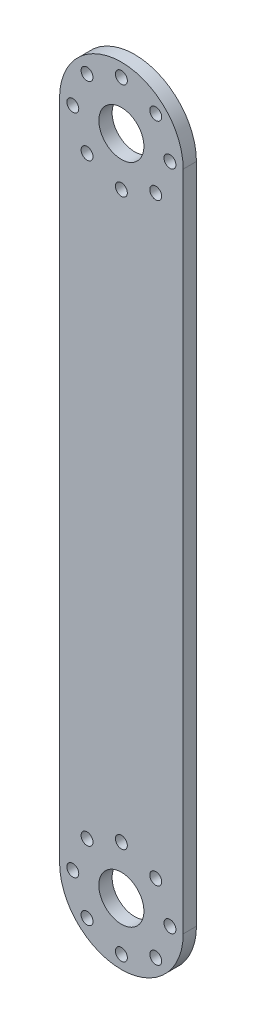
SolidWorks part; units mm, degrees
ref_plane "前视基准面" through (0, 0, 0) normal (0, 0, 1) x (1, 0, 0)
ref_plane "上视基准面" through (0, 0, 0) normal (0, 1, 0) x (1, 0, 0)
ref_plane "右视基准面" through (0, 0, 0) normal (1, 0, 0) x (0, 0, -1)
sketch "草图1" plane through (0, 0, 0) normal (0, 0, 1) x (1, 0, 0)
  line L0 (-14, 0) -> (-14, 150)
  line L1 (14, 0) -> (14, 150)
  line L2 (0, -18.9873) -> (0, 57.2937) construction
  arc A0 (-14, 0) -> (14, 0) centre (0, 0) ccw
  arc A1 (14, 150) -> (-14, 150) centre (0, 150) ccw
  circle A2 centre (0, 161) radius 1.35
  circle A3 centre (7.7782, 157.7782) radius 1.35
  circle A4 centre (11, 150) radius 1.35
  circle A5 centre (7.7782, 142.2218) radius 1.35
  circle A6 centre (0, 139) radius 1.35
  circle A7 centre (-7.7782, 142.2218) radius 1.35
  circle A8 centre (-11, 150) radius 1.35
  circle A9 centre (-7.7782, 157.7782) radius 1.35
  circle A10 centre (0, 150) radius 5.1
  circle A11 centre (0, 0) radius 5.1
  circle A12 centre (0, -11) radius 1.35
  circle A13 centre (-7.7782, -7.7782) radius 1.35
  circle A14 centre (-11, 0) radius 1.35
  circle A15 centre (-7.7782, 7.7782) radius 1.35
  circle A16 centre (0, 11) radius 1.35
  circle A17 centre (7.7782, 7.7782) radius 1.35
  circle A18 centre (11, 0) radius 1.35
  circle A19 centre (7.7782, -7.7782) radius 1.35
  point P27 (0, 150)
  point P46 (0, 0)
  dimension "D1" = 28
  dimension "D3" = 2.7
  dimension "D6" = 10.2
  dimension "D7" = 2.7
  dimension "D10" = 10.2
  dimension "D2" = 150
  dimension "D4" = 11
  dimension "D8" = 11
  dimension "D5" = 8
  dimension "D9" = 8
extrude "凸台-拉伸1" add sketch "草图1" along normal blind 3
